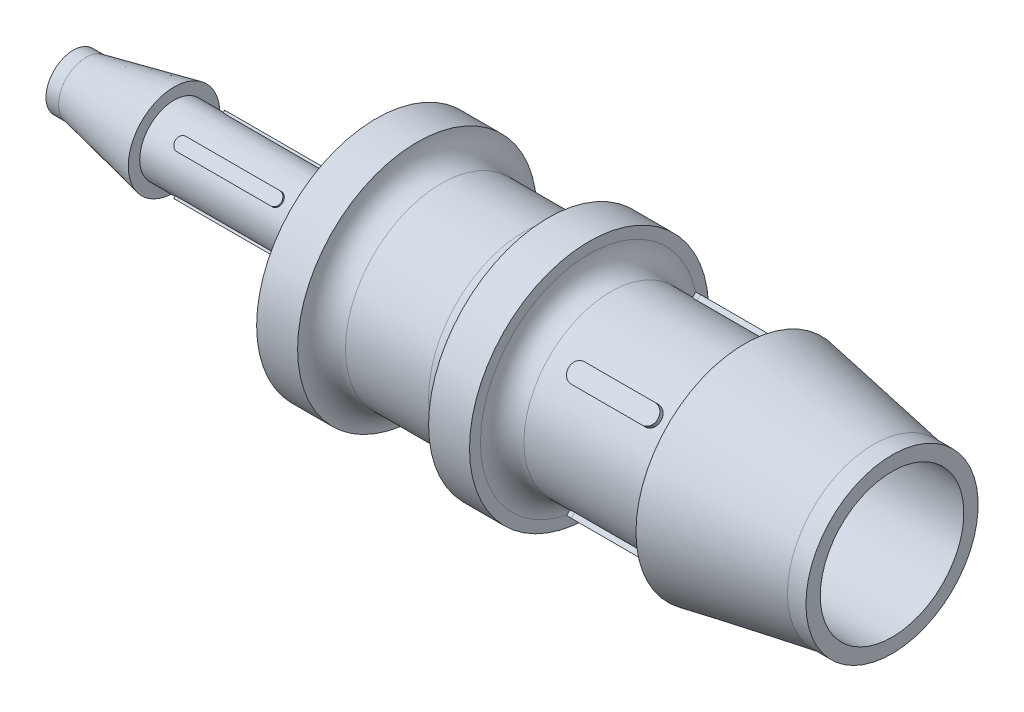
SolidWorks part; units mm, degrees
ref_plane "Front Plane" through (0, 0, 0) normal (0, 0, 1) x (1, 0, 0)
ref_plane "Top Plane" through (0, 0, 0) normal (0, 1, 0) x (1, 0, 0)
ref_plane "Right Plane" through (0, 0, 0) normal (1, 0, 0) x (0, 0, -1)
sketch "Sketch1" plane through (0, 0, 0) normal (0, 0, 1) x (1, 0, 0)
  line L0 (0, 0) -> (34.0487, 0) construction
  line L1 (34.0487, 5.969) -> (34.0487, 7.1628)
  line L2 (-8.8527, 2.8575) -> (-8.8527, 9.9466)
  line L3 (21.7912, 9.0424) -> (21.7912, 7.2339)
  line L4 (21.7912, 7.2339) -> (8.8527, 7.2339)
  line L5 (34.0487, 7.1628) -> (32.5165, 7.1628)
  line L6 (8.8527, 7.2339) -> (8.8527, 9.9466)
  line L7 (8.8527, 9.9466) -> (5.4478, 9.9466)
  line L8 (5.4478, 9.9466) -> (5.4478, 7.9573)
  line L9 (5.4478, 7.9573) -> (-5.4478, 7.9573)
  line L10 (34.0487, 5.969) -> (-5.4478, 5.969)
  line L11 (0, 1.4605) -> (0, 7.9573) construction
  line L12 (15.7764, 8.1382) -> (21.7912, 8.1382) construction
  line L13 (0, 0) -> (0, -2.6412) construction
  line L14 (32.5165, 7.1628) -> (21.7912, 9.0424)
  line L15 (-8.8527, 9.9466) -> (-5.4478, 9.9466)
  line L16 (-5.4478, 9.9466) -> (-5.4478, 7.9573)
  line L17 (-34.0487, 1.8161) -> (-5.4478, 1.8161)
  line L18 (-34.0487, 1.8161) -> (-34.0487, 2.2701)
  line L19 (-34.0487, 2.2701) -> (-33.001, 2.2701)
  line L20 (-33.001, 2.2701) -> (-25.6667, 3.81)
  line L21 (-25.6667, 3.81) -> (-25.6667, 2.8575)
  line L22 (-25.6667, 2.8575) -> (-8.8527, 2.8575)
  line L23 (-5.4478, 1.8161) -> (-5.4478, 5.969)
  line L24 (-34.0487, 7.7522) -> (-34.0487, -1.9104) construction
  dimension "D1" = 14.3256
  dimension "D7" = 15.9146
  dimension "D3" = 12.2575
  dimension "D8" = 1.5322
  dimension "D9" = 68.0974
  dimension "A1" = 3.6322
  dimension "B1" = 7.62
  dimension "D10" = 8.382
  dimension "D11" = 1.0478
  dimension "D12" = 4.5403
  dimension "D13" = 5.715
revolve "Revolve1" add sketch "Sketch1" angle 360 about L0
sketch "Sketch2" plane through (0, 0, 0) normal (0, 0, 1) x (1, 0, 0)
  line L0 (21.7912, 7.2339) -> (8.8527, 7.2339) construction
  line L1 (8.8527, 7.2339) -> (8.8527, 9.9466) construction
  line L2 (10.6611, 7.2339) -> (8.8527, 7.2339)
  line L3 (8.8527, 7.2339) -> (8.8527, 9.0424)
  line L4 (5.4478, 9.9466) -> (5.4478, 7.9573) construction
  line L5 (5.4478, 7.9573) -> (-5.4478, 7.9573) construction
  line L6 (5.4478, 9.9466) -> (5.4478, 7.9573)
  line L7 (5.4478, 7.9573) -> (3.4585, 7.9573)
  line L8 (-5.4478, 9.9466) -> (-5.4478, 7.9573) construction
  line L9 (-25.6667, 2.8575) -> (-8.8527, 2.8575) construction
  line L10 (-8.8527, 2.8575) -> (-8.8527, 9.9466) construction
  line L11 (-5.4478, 9.9466) -> (-5.4478, 7.9573)
  line L12 (-12.3972, 2.8575) -> (-8.8527, 2.8575)
  line L13 (-8.8527, 2.8575) -> (-8.8527, 6.4021)
  line L14 (-5.4478, 7.9573) -> (-3.4585, 7.9573)
  line L15 (7.2593, 9.9466) -> (7.2593, 9.0424) construction
  line L16 (7.2593, 9.0424) -> (7.0891, 9.0424) construction
  line L17 (7.0891, 9.0424) -> (7.0891, 8.1382) construction
  line L18 (7.0891, 8.1382) -> (7.2706, 8.1382) construction
  line L19 (7.2706, 8.1382) -> (7.2706, 7.2339) construction
  arc A0 (8.8527, 9.0424) -> (10.6611, 7.2339) centre (10.6611, 9.0424) ccw
  arc A1 (5.4478, 9.9466) -> (3.4585, 7.9573) centre (3.4585, 9.9466) cw
  arc A2 (-8.8527, 6.4021) -> (-12.3972, 2.8575) centre (-12.3972, 6.4021) cw
  arc A3 (-5.4478, 9.9466) -> (-3.4585, 7.9573) centre (-3.4585, 9.9466) ccw
revolve "Revolve2" add sketch "Sketch2" angle 360 about L0
ref_plane "Plane1" through (0, 0, 0) normal (0, 0.7071, 0.7071) x (-1, 0, 0)
sketch "Sketch3" plane through (0, 0, 0) normal (0, 0.7071, 0.7071) x (-1, 0, 0)
  line L0 (0, 0) -> (-34.0487, 0) construction
  line L1 (-13.2822, 0.7661) -> (-19.1701, 0.7661)
  line L2 (-13.2822, 0.7661) -> (-13.2822, -0.7661) construction
  line L3 (-13.2822, -0.7661) -> (-19.1701, -0.7661)
  line L4 (-19.1701, 0.7661) -> (-19.1701, -0.7661) construction
  line L5 (-12.5161, 3.344) -> (-12.5161, -2.3159) construction
  line L6 (-14.3712, 4.5434) -> (-18.0812, 4.5434) construction
  line L7 (-18.0812, 3.344) -> (-18.0812, 4.5434) construction
  line L8 (-16.2262, 4.5434) -> (-16.2262, 0.7661) construction
  line L9 (-10.6611, 3.344) -> (-14.3712, 3.344) construction
  line L10 (12.3972, 3.2566) -> (16.8204, 3.2566) construction
  line L11 (-21.7912, 3.344) -> (-18.0812, 3.344) construction
  line L12 (16.8204, 3.2566) -> (16.8204, 4.0351) construction
  line L13 (-14.3712, 4.5434) -> (-14.3712, 3.344) construction
  line L14 (16.8204, 4.0351) -> (21.2435, 4.0351) construction
  line L15 (21.2435, 4.0351) -> (21.2435, 3.344) construction
  line L16 (21.2435, 3.344) -> (25.6667, 3.344) construction
  line L17 (19.032, 4.0351) -> (19.032, 0.5239) construction
  line L19 (15.1327, 0.5239) -> (22.9312, 0.5239) construction
  line L20 (15.1327, 0.5239) -> (15.1327, -0.5239) construction
  line L21 (15.1327, -0.5239) -> (22.9312, -0.5239) construction
  line L22 (22.9312, 0.5239) -> (22.9312, -0.5239) construction
  line L23 (14.6088, 3.2566) -> (14.6088, -1.2294) construction
  line L24 (0, 0) -> (24.6192, 0) construction
  arc A0 (-19.1701, 0.7661) -> (-19.1701, -0.7661) centre (-19.1701, 0) ccw
  arc A1 (-13.2822, 0.7661) -> (-13.2822, -0.7661) centre (-13.2822, 0) cw
  arc A2 (22.9312, 0.5239) -> (22.9312, -0.5239) centre (22.9312, 0) cw construction
  arc A3 (15.1327, 0.5239) -> (15.1327, -0.5239) centre (15.1327, 0) ccw construction
  dimension "D1" = 1.5322
  dimension "D2" = 1.0478
extrude "Extrude1" add sketch "Sketch3" along normal mid plane 15.1912
sketch "Sketch6" plane through (0, 0, 0) normal (0, 0.7071, 0.7071) x (-1, 0, 0)
  line L0 (15.1327, 0.5239) -> (22.9312, 0.5239) construction
  line L1 (15.1327, -0.5239) -> (22.9312, -0.5239) construction
  line L2 (15.1327, 0.5239) -> (22.9312, 0.5239)
  line L3 (15.1327, -0.5239) -> (22.9312, -0.5239)
  arc A0 (22.9312, -0.5239) -> (22.9312, 0.5239) centre (22.9312, 0) ccw construction
  arc A1 (15.1327, 0.5239) -> (15.1327, -0.5239) centre (15.1327, 0) ccw construction
  arc A2 (22.9312, -0.5239) -> (22.9312, 0.5239) centre (22.9312, 0) ccw
  arc A3 (15.1327, 0.5239) -> (15.1327, -0.5239) centre (15.1327, 0) ccw
extrude "Extrude2" add sketch "Sketch6" along normal mid plane 6.0007
pattern_circular "CirPattern1" count 2 every 90 about axis through (0, 0, 0) along (1, 0, 0) of "Extrude1", "Extrude2"
sketch "Sketch4" plane through (34.0487, 0, 0) normal (1, 0, 0) x (0, 0, -1)
  circle A0 centre (0, 0) radius 5.969 construction
  circle A1 centre (0, 0) radius 5.969
extrude "Cut-Extrude1" cut sketch "Sketch4" against normal up to vertex (39.4965 mm away) up to point (-5.4478, 7.9573, 0)
sketch "Sketch7" plane through (-34.0487, 0, 0) normal (-1, 0, 0) x (0, 0, 1)
  circle A0 centre (0, 0) radius 1.8161 construction
  circle A1 centre (0, 0) radius 1.8161
extrude "Cut-Extrude2" cut sketch "Sketch7" against normal through all
equation "\"D1@Sketch1\" = \"A@Sketch1\"*1.2"
equation "\"D3@Sketch1\" = \"C@Sketch1\"*.18"
equation "\"D4@Sketch1\" = \"C@Sketch1\"*.05"
equation "\"D6@Sketch1\" = \"C@Sketch1\"*.160/2"
equation "\"D2@Sketch1\" = \"B@Sketch1\"*.8"
equation "\"D5@Sketch1\" = \"B@Sketch1\"*1.1"
equation "\"D7@Sketch1\" = \"D2@Sketch1\"*1.1"
equation "\"D8@Sketch1\" = \"D3@Sketch1\"/8"
equation "\"D1@Sketch3\" = \"D8@Sketch1\""
equation "\"D1@Extrude1\" = \"D2@Sketch1\"*1.05"
equation "\"D9@Sketch1\" = \"C@Sketch1\""
equation "\"D10@Sketch1\" = \"B1@Sketch1\"*1.1"
equation "\"D11@Sketch1\" = \"D10@Sketch1\"/8"
equation "\"D12@Sketch1\" = \"A1@Sketch1\"*1.25"
equation "\"D13@Sketch1\" = \"B1@Sketch1\"*.750"
equation "\"D2@Sketch3\" = \"D11@Sketch1\""
equation "\"D1@Extrude2\" = \"D13@Sketch1\"*1.05"
